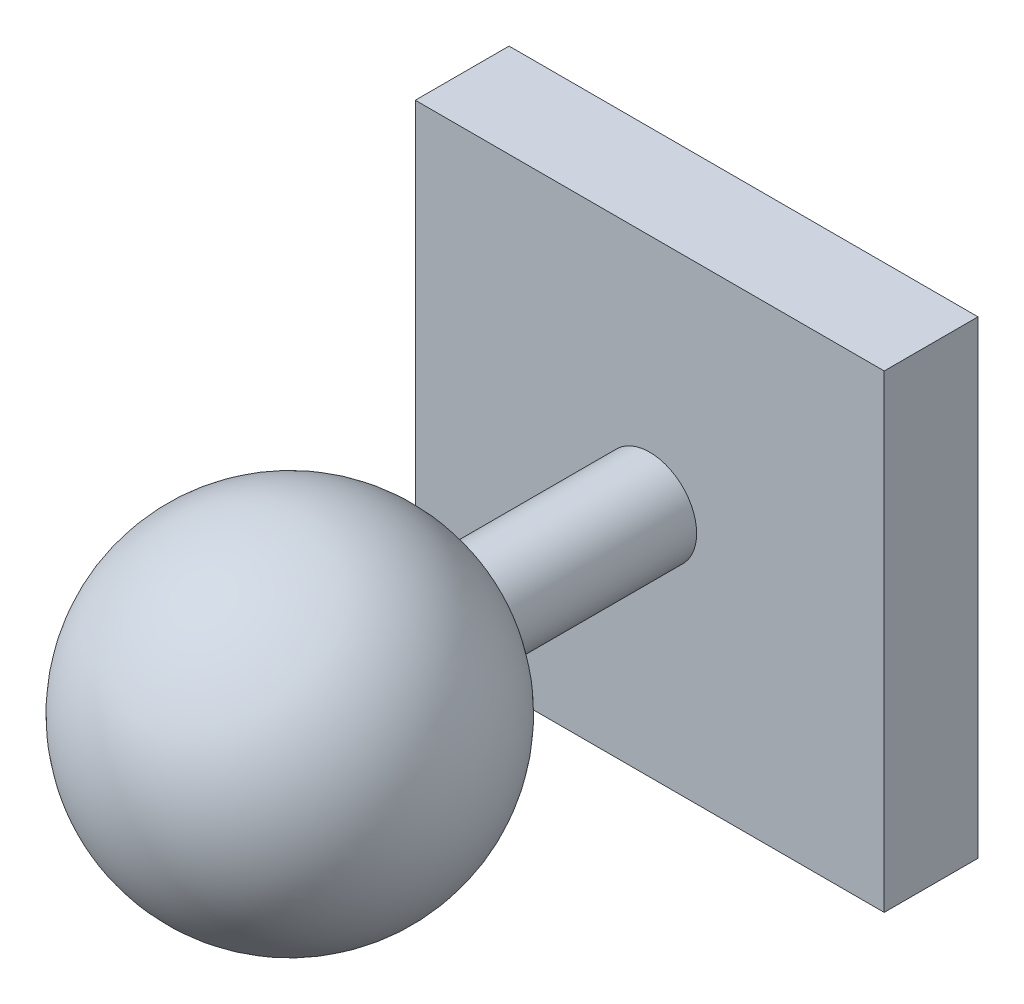
SolidWorks part; units mm, degrees
ref_plane "前视基准面" through (0, 0, 0) normal (0, 0, 1) x (1, 0, 0)
ref_plane "上视基准面" through (0, 0, 0) normal (0, 1, 0) x (1, 0, 0)
ref_plane "右视基准面" through (0, 0, 0) normal (1, 0, 0) x (0, 0, -1)
sketch "草图1" plane through (0, 0, 0) normal (0, 0, 1) x (1, 0, 0)
  line L1 (25, -25) -> (-25, -25)
  line L2 (25, -25) -> (25, 25)
  line L3 (25, 25) -> (-25, 25)
  line L4 (-25, -25) -> (-25, 25)
  line L5 (25, -25) -> (-25, 25) construction
  line L6 (25, 25) -> (-25, -25) construction
  point P0 (0, 0)
  dimension "D1" = 50
  dimension "D2" = 50
extrude "凸台-拉伸1" add sketch "草图1" along normal blind 10
sketch "草图2" plane through (0, 0, 10) normal (0, 0, 1) x (1, 0, 0)
  circle A0 centre (0, 0) radius 5
extrude "凸台-拉伸2" add sketch "草图2" along normal blind 20
sketch "草图4" plane through (0, 0, 0) normal (0, 1, 0) x (1, 0, 0)
  line L0 (0, -30) -> (0, -66.7661)
  arc A0 (0, -30) -> (0, -66.7661) centre (0, -48.3831) ccw
revolve "旋转16" add sketch "草图4" angle 360 about L0
sketch "草图5" plane through (0, 0, 0) normal (0, 0, -1) x (-1, 0, 0)
  circle A0 centre (0, 0) radius 5
extrude "切除-拉伸3" cut sketch "草图5" against normal blind 5
